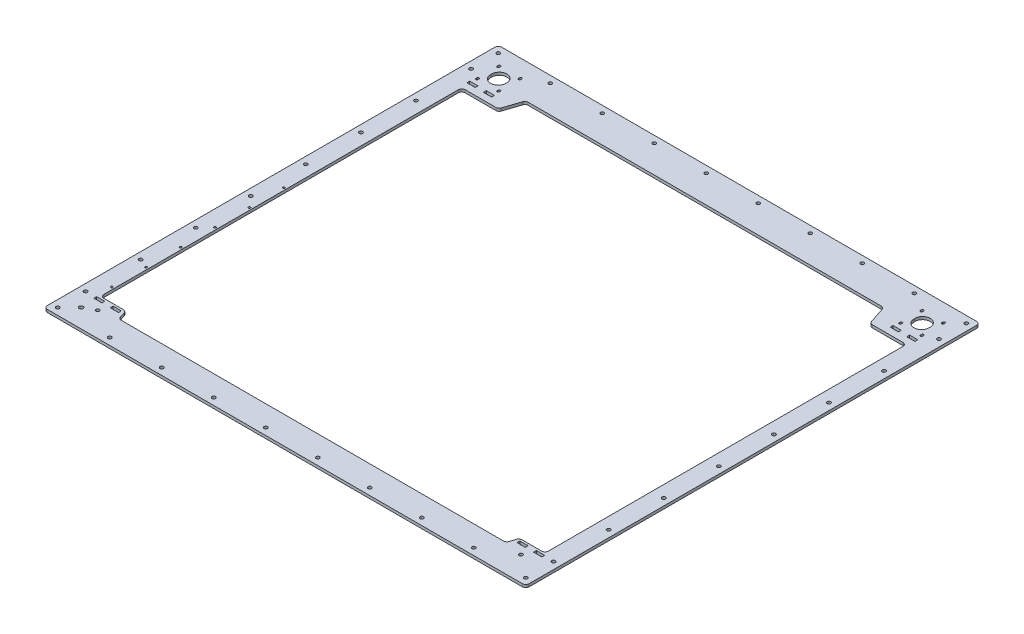
SolidWorks part; units mm, degrees
ref_plane "Front Plane" through (0, 0, 0) normal (0, 0, 1) x (1, 0, 0)
ref_plane "Top Plane" through (0, 0, 0) normal (0, 1, 0) x (1, 0, 0)
ref_plane "Right Plane" through (0, 0, 0) normal (1, 0, 0) x (0, 0, -1)
sketch "Sketch2" plane through (0, 0, 0) normal (0, 1, 0) x (1, 0, 0)
  line L0 (-305.65, 287.85) -> (-305.65, 286.25)
  line L1 (-308.85, 287.85) -> (-308.85, 286.25)
  line L2 (329.25, 264.25) -> (329.25, -260.75) construction
  line L3 (-274.65, 287.85) -> (-274.65, 286.25)
  line L4 (289.3538, 264.25) -> (333.75, 264.25)
  line L5 (-302.25, 264.25) -> (-257.8538, 264.25)
  line L6 (-307.25, -255.75) -> (-307.25, 259.25)
  line L7 (-277.85, 287.85) -> (-277.85, 286.25)
  line L8 (-235, -250.75) -> (-235, 249.25) construction
  line L9 (-235, -250.75) -> (265, -250.75) construction
  line L10 (-240.6462, 294.25) -> (272.1462, 294.25)
  line L11 (265, -250.75) -> (265, 249.25) construction
  line L12 (-235, 249.25) -> (265, 249.25) construction
  line L13 (293.4506, -275.75) -> (-261.9506, -275.75)
  line L14 (-235, -250.75) -> (265, 249.25) construction
  line L15 (265, -250.75) -> (-235, 249.25) construction
  line L16 (-274.65, 318.85) -> (-274.65, 317.25)
  line L17 (-277.85, 318.85) -> (-277.85, 317.25)
  line L18 (-329.25, 344.25) -> (360.75, 344.25)
  line L19 (365.75, 339.25) -> (365.75, -310.75)
  line L20 (360.75, -315.75) -> (-329.25, -315.75)
  line L21 (-334.25, -310.75) -> (-334.25, 339.25)
  line L22 (-305.65, 318.85) -> (-305.65, 317.25)
  line L23 (-297.75, 264.25) -> (-297.75, 248.2516) construction
  line L24 (-308.85, 318.85) -> (-308.85, 317.25)
  line L25 (-285.75, -260.75) -> (-285.75, 183.2516) construction
  line L26 (-245.3896, 290.8311) -> (-253.1104, 267.6689)
  line L27 (276.8896, 290.8311) -> (284.6104, 267.6689)
  line L28 (-273.9456, -260.75) -> (-302.25, -260.75)
  line L29 (338.75, -255.75) -> (338.75, 259.25)
  line L30 (317.25, -260.75) -> (317.25, 264.25) construction
  line L31 (305.4456, -260.75) -> (333.75, -260.75)
  line L32 (300.6657, -264.2829) -> (298.2305, -272.2171)
  line L33 (-269.1657, -264.2829) -> (-266.7305, -272.2171)
  line L34 (309.35, 287.85) -> (309.35, 286.25)
  line L35 (-280.7, 303.35) -> (-280.7, 301.75)
  line L36 (-302.8, 303.35) -> (-302.8, 301.75)
  line L37 (306.15, 287.85) -> (306.15, 286.25)
  line L38 (340.35, 287.85) -> (340.35, 286.25)
  line L39 (337.15, 287.85) -> (337.15, 286.25)
  line L40 (340.35, 318.85) -> (340.35, 317.25)
  line L41 (337.15, 318.85) -> (337.15, 317.25)
  line L42 (309.35, 318.85) -> (309.35, 317.25)
  line L43 (306.15, 318.85) -> (306.15, 317.25)
  line L44 (334.3, 301.7902) -> (334.3, 301.75)
  line L45 (312.2, 301.7902) -> (312.2, 301.75)
  line L46 (334.3, 303.35) -> (334.3, 301.75)
  line L47 (-314.25, -295.75) -> (-314.25, 324.25) construction
  line L48 (345.75, -295.75) -> (345.75, 324.25) construction
  line L49 (345.75, 324.25) -> (-314.25, 324.25) construction
  line L50 (345.75, -295.75) -> (-314.25, -295.75) construction
  line L51 (312.2, 303.35) -> (312.2, 301.75)
  line L52 (305.25, -263.8637) -> (305.25, -267.9637)
  line L53 (305.25, 278.35) -> (305.25, 274.25)
  line L54 (317.25, 278.35) -> (305.25, 278.35)
  line L55 (-309.75, 274.25) -> (-309.75, 278.35)
  line L56 (-309.75, 278.35) -> (-297.75, 278.35)
  line L57 (-297.75, 278.35) -> (-297.75, 274.25)
  line L58 (-297.75, 274.25) -> (-309.75, 274.25)
  line L59 (-285.75, 274.25) -> (-273.75, 274.25)
  line L60 (-285.75, 274.25) -> (-285.75, 278.35)
  line L61 (-285.75, 278.35) -> (-273.75, 278.35)
  line L62 (-273.75, 278.35) -> (-273.75, 274.25)
  line L63 (317.25, 274.25) -> (317.25, 278.35)
  line L64 (317.25, 274.25) -> (305.25, 274.25)
  line L65 (329.25, 274.25) -> (341.25, 274.25)
  line L66 (329.25, 278.35) -> (329.25, 274.25)
  line L67 (341.25, 278.35) -> (329.25, 278.35)
  line L68 (341.25, 274.25) -> (341.25, 278.35)
  line L69 (317.25, -263.8637) -> (305.25, -263.8637)
  line L70 (317.25, -267.9637) -> (317.25, -263.8637)
  line L71 (317.25, -267.9637) -> (305.25, -267.9637)
  line L72 (329.25, -267.9637) -> (341.25, -267.9637)
  line L73 (329.25, -263.8637) -> (329.25, -267.9637)
  line L74 (341.25, -263.8637) -> (329.25, -263.8637)
  line L75 (341.25, -267.9637) -> (341.25, -263.8637)
  line L76 (-285.75, 248.2516) -> (-285.75, 264.25) construction
  line L77 (-309.75, -267.9637) -> (-309.75, -263.8637)
  line L78 (-309.75, -263.8637) -> (-297.75, -263.8637)
  line L79 (-297.75, -263.8637) -> (-297.75, -267.9637)
  line L80 (-297.75, -267.9637) -> (-309.75, -267.9637)
  line L81 (-285.75, -267.9637) -> (-273.75, -267.9637)
  line L82 (-285.75, -267.9637) -> (-285.75, -263.8637)
  line L83 (-285.75, -263.8637) -> (-273.75, -263.8637)
  line L84 (-273.75, -263.8637) -> (-273.75, -267.9637)
  line L94 (-297.75, 183.2516) -> (-297.75, -260.75) construction
  arc A0 (272.1462, 294.25) -> (276.8896, 290.8311) centre (272.1462, 289.25) cw
  arc A1 (284.6104, 267.6689) -> (289.3538, 264.25) centre (289.3538, 269.25) ccw
  arc A2 (-240.6462, 294.25) -> (-245.3896, 290.8311) centre (-240.6462, 289.25) ccw
  arc A3 (-253.1104, 267.6689) -> (-257.8538, 264.25) centre (-257.8538, 269.25) cw
  arc A4 (293.4506, -275.75) -> (298.2305, -272.2171) centre (293.4506, -270.75) ccw
  arc A5 (305.4456, -260.75) -> (300.6657, -264.2829) centre (305.4456, -265.75) ccw
  arc A6 (-261.9506, -275.75) -> (-266.7305, -272.2171) centre (-261.9506, -270.75) cw
  arc A7 (-273.9456, -260.75) -> (-269.1657, -264.2829) centre (-273.9456, -265.75) cw
  arc A8 (-302.25, -260.75) -> (-307.25, -255.75) centre (-302.25, -255.75) cw
  arc A9 (-307.25, 259.25) -> (-302.25, 264.25) centre (-302.25, 259.25) cw
  arc A10 (338.75, 259.25) -> (333.75, 264.25) centre (333.75, 259.25) ccw
  arc A11 (333.75, -260.75) -> (338.75, -255.75) centre (333.75, -255.75) ccw
  circle A12 centre (-291.75, 301.75) radius 8.9 construction
  circle A13 centre (323.25, 301.75) radius 8.9 construction
  circle A14 centre (-291.75, -280.25) radius 8.9 construction
  circle A15 centre (323.25, -280.25) radius 8.9 construction
  arc A16 (-329.25, -315.75) -> (-334.25, -310.75) centre (-329.25, -310.75) cw
  arc A17 (365.75, -310.75) -> (360.75, -315.75) centre (360.75, -310.75) cw
  arc A18 (360.75, 344.25) -> (365.75, 339.25) centre (360.75, 339.25) cw
  arc A19 (-329.25, 344.25) -> (-334.25, 339.25) centre (-329.25, 339.25) ccw
  arc A20 (-308.85, 317.25) -> (-305.65, 317.25) centre (-307.25, 317.25) ccw
  arc A21 (-277.85, 317.25) -> (-274.65, 317.25) centre (-276.25, 317.25) ccw
  arc A22 (-277.85, 286.25) -> (-274.65, 286.25) centre (-276.25, 286.25) ccw
  arc A23 (-308.85, 286.25) -> (-305.65, 286.25) centre (-307.25, 286.25) ccw
  arc A24 (-305.65, 318.85) -> (-308.85, 318.85) centre (-307.25, 318.85) ccw
  arc A25 (-274.65, 318.85) -> (-277.85, 318.85) centre (-276.25, 318.85) ccw
  arc A26 (-305.65, 287.85) -> (-308.85, 287.85) centre (-307.25, 287.85) ccw
  arc A27 (-274.65, 287.85) -> (-277.85, 287.85) centre (-276.25, 287.85) ccw
  arc A28 (-302.8, 301.75) -> (-280.7, 301.75) centre (-291.75, 301.75) ccw
  arc A29 (-280.7, 303.35) -> (-302.8, 303.35) centre (-291.75, 303.35) ccw
  circle A30 centre (323.25, 301.75) radius 8.9 construction
  arc A31 (306.15, 317.25) -> (309.35, 317.25) centre (307.75, 317.25) ccw
  arc A32 (337.15, 317.25) -> (340.35, 317.25) centre (338.75, 317.25) ccw
  arc A33 (337.15, 286.25) -> (340.35, 286.25) centre (338.75, 286.25) ccw
  arc A34 (306.15, 286.25) -> (309.35, 286.25) centre (307.75, 286.25) ccw
  arc A35 (309.35, 318.85) -> (306.15, 318.85) centre (307.75, 318.85) ccw
  arc A36 (340.35, 318.85) -> (337.15, 318.85) centre (338.75, 318.85) ccw
  arc A37 (309.35, 287.85) -> (306.15, 287.85) centre (307.75, 287.85) ccw
  arc A38 (340.35, 287.85) -> (337.15, 287.85) centre (338.75, 287.85) ccw
  arc A39 (312.2, 301.75) -> (334.3, 301.75) centre (323.25, 301.75) ccw
  circle A40 centre (-307.25, -288.75) radius 3
  circle A41 centre (-324.25, 334.25) radius 2.55
  circle A42 centre (-248.69, 334.25) radius 2.55
  circle A43 centre (-173.13, 334.25) radius 2.55
  circle A44 centre (-97.57, 334.25) radius 2.55
  circle A45 centre (-22.01, 334.25) radius 2.55
  circle A46 centre (53.55, 334.25) radius 2.55
  circle A47 centre (129.11, 334.25) radius 2.55
  circle A48 centre (204.67, 334.25) radius 2.55
  circle A49 centre (280.23, 334.25) radius 2.55
  circle A50 centre (355.79, 334.25) radius 2.55
  circle A51 centre (355.79, -305.75) radius 2.55
  circle A52 centre (280.23, -305.75) radius 2.55
  circle A53 centre (204.67, -305.75) radius 2.55
  circle A54 centre (129.11, -305.75) radius 2.55
  circle A55 centre (53.55, -305.75) radius 2.55
  circle A56 centre (-22.01, -305.75) radius 2.55
  circle A57 centre (-97.57, -305.75) radius 2.55
  circle A58 centre (-173.13, -305.75) radius 2.55
  circle A59 centre (-248.69, -305.75) radius 2.55
  circle A60 centre (-324.25, -305.75) radius 2.55
  circle A61 centre (-324.25, 294.75) radius 2.55
  circle A62 centre (-324.25, 214.75) radius 2.55
  circle A63 centre (-324.25, 134.75) radius 2.55
  circle A64 centre (-324.25, 54.75) radius 2.55
  circle A65 centre (-324.25, -25.25) radius 2.55
  circle A66 centre (-324.25, -105.25) radius 2.55
  circle A67 centre (-324.25, -185.25) radius 2.55
  circle A68 centre (-324.25, -265.25) radius 2.55
  circle A69 centre (355.75, -265.25) radius 2.55
  circle A70 centre (355.75, -185.25) radius 2.55
  circle A71 centre (355.75, -105.25) radius 2.55
  circle A72 centre (355.75, -25.25) radius 2.55
  circle A73 centre (355.75, 54.75) radius 2.55
  circle A74 centre (355.75, 134.75) radius 2.55
  circle A75 centre (355.75, 214.75) radius 2.55
  circle A76 centre (355.75, 294.75) radius 2.55
  circle A77 centre (-291.75, -280.25) radius 2.55
  circle A78 centre (323.25, -280.25) radius 2.55
  circle A79 centre (323.25, 301.75) radius 8.9 construction
  arc A80 (312.2, 301.75) -> (334.3, 301.75) centre (323.25, 301.75) ccw
  arc A81 (334.3, 303.35) -> (312.2, 303.35) centre (323.25, 303.35) ccw
  circle A82 centre (-310.75, -240.75) radius 1.5
  circle A83 centre (-310.75, -190.75) radius 1.5
  circle A84 centre (-310.75, -140.75) radius 1.5
  circle A85 centre (-310.75, -90.75) radius 1.5
  circle A86 centre (-310.75, -40.75) radius 1.5
  circle A87 centre (-310.75, 9.25) radius 1.5
  dimension "D1" = 5
  dimension "D2" = 5
  dimension "D3" = 5
  dimension "D4" = 5
  dimension "D5" = 5
  dimension "D6" = 10
  dimension "D7" = 8
extrude "Boss-Extrude1" add sketch "Sketch2" along normal blind 4 contours L18 A19 L21 A16 L20 A17 L19 A18 A78 A77 A75 A73 A71 A69 A68 A67 A66 A65 A64 A63 A62 A61 A59 A57 A55 A53 A51 A50 A49
